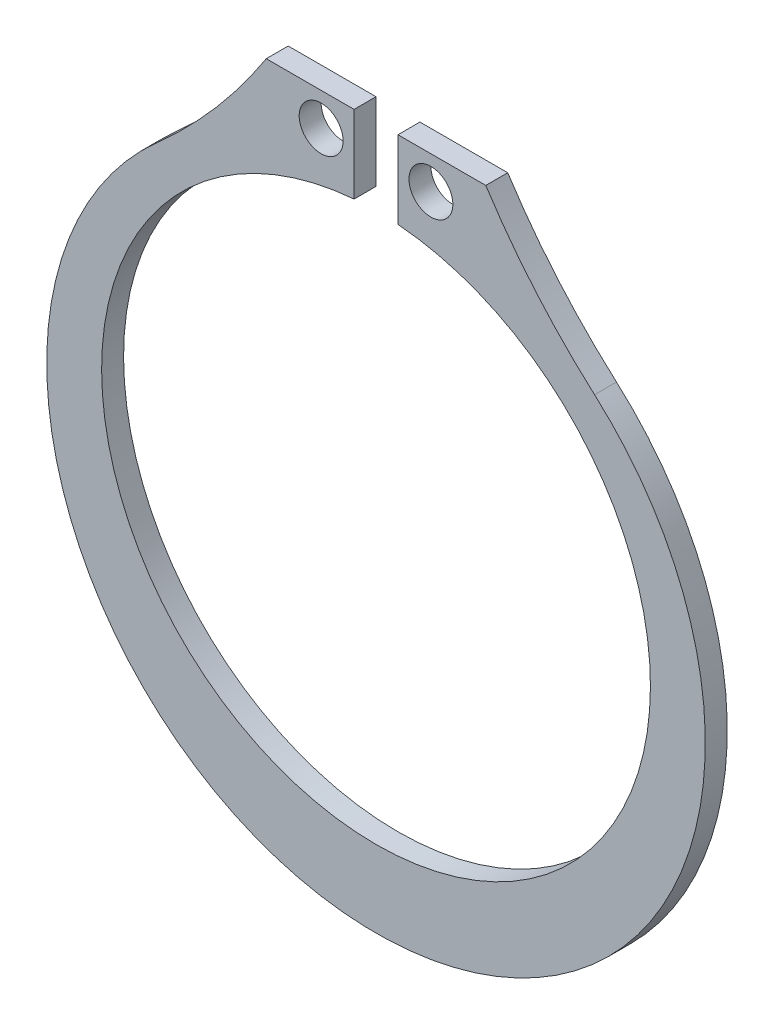
SolidWorks part; units mm, degrees
material "Alloy Steel"
ref_plane "Front Plane" through (0, 0, 0) normal (0, 0, 1) x (1, 0, 0)
ref_plane "Top Plane" through (0, 0, 0) normal (0, 1, 0) x (1, 0, 0)
ref_plane "Right Plane" through (0, 0, 0) normal (1, 0, 0) x (0, 0, -1)
sketch "Sketch1" plane through (0, 0, 0) normal (0, 0, 1) x (1, 0, 0)
  line L0 (0, 0) -> (0, 6.0682) construction
  line L1 (-5, 17) -> (-1, 17)
  line L2 (-1, 17) -> (-1, 13.4599)
  line L3 (1, 17) -> (1, 13.4599)
  line L4 (5, 17) -> (1, 17)
  arc A0 (-9.9549, 11.2205) -> (9.9549, 11.2205) centre (0, 0) ccw
  arc A1 (-1, 13.4599) -> (1, 13.4599) centre (0, 1) ccw
  arc A2 (-5, 17) -> (-9.9549, 11.2205) centre (-28.5374, 32.1655) cw
  arc A3 (5, 17) -> (9.9549, 11.2205) centre (28.5374, 32.1655) ccw
  circle A4 centre (-2.5, 15.5) radius 1
  circle A5 centre (2.5, 15.5) radius 1
  dimension "D1" = 1
  dimension "D4" = 25
  dimension "D5" = 30
  dimension "D6" = 28
  dimension "D8" = 2
  dimension "D2" = 10
  dimension "D3" = 16
  dimension "D7" = 2
  dimension "D9" = 1.5
  dimension "D10" = 1.5
extrude "Boss-Extrude1" add sketch "Sketch1" along normal blind 1
